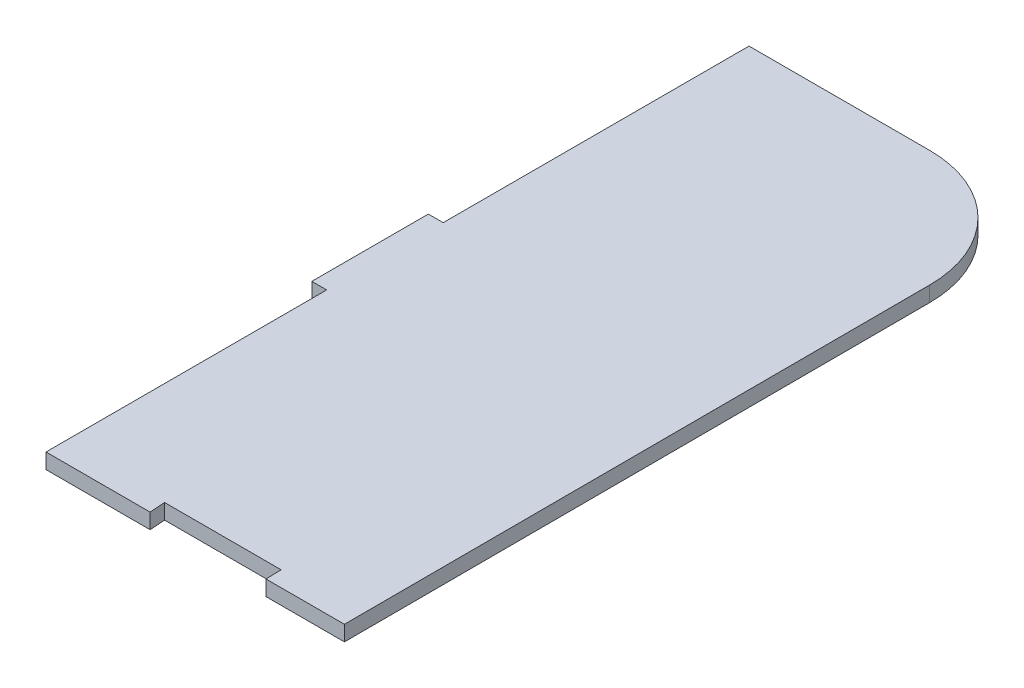
SolidWorks part; units mm, degrees
ref_plane "Front Plane" through (0, 0, 0) normal (0, 0, 1) x (1, 0, 0)
ref_plane "Top Plane" through (0, 0, 0) normal (0, 1, 0) x (1, 0, 0)
ref_plane "Right Plane" through (0, 0, 0) normal (1, 0, 0) x (0, 0, -1)
sketch "Sketch1" plane through (0, 0, 0) normal (0, 0, 1) x (1, 0, 0)
  line L0 (358.1218, 1488.44) -> (358.1218, 20.32) construction
  line L1 (358.1218, 754.38) -> (137.9613, 754.38)
  line L2 (358.1218, 754.38) -> (562.8036, 754.38)
  line L3 (562.8036, 754.38) -> (562.8036, 744.38)
  line L4 (562.8036, 744.38) -> (137.9613, 744.38)
  line L5 (137.9613, 744.38) -> (137.9613, 754.38)
  dimension "D1" = 10
extrude "Boss-Extrude1" add sketch "Sketch1" along normal up to surface (459.74 mm away)
sketch "Sketch3" plane through (0, 744.38, 0) normal (0, -1, 0) x (1, 0, 0)
  line L0 (255.63, 0) -> (255.63, 459.74)
  line L1 (137.9613, 0) -> (562.8036, 0) construction
  line L2 (137.9613, 459.74) -> (562.8036, 459.74) construction
  line L3 (255.63, 459.74) -> (137.9613, 459.74)
  line L4 (137.9613, 459.74) -> (137.9613, 0)
  line L5 (137.9613, 0) -> (255.63, 0)
extrude "Cut-Extrude1" cut sketch "Sketch3" against normal blind 10
sketch "Sketch4" plane through (0, 754.38, 0) normal (0, 1, 0) x (1, 0, 0)
  line L0 (265.3552, -459.74) -> (265.3552, -276.2)
  line L1 (562.8036, -459.74) -> (255.63, -459.74) construction
  line L2 (562.8036, 0) -> (255.63, 0) construction
  line L3 (265.3552, -459.74) -> (255.63, -459.74)
  line L4 (255.63, -459.74) -> (255.63, -276.2)
  line L5 (215.8296, -276.2) -> (265.3552, -276.2) construction
  line L6 (215.8296, -200) -> (265.3552, -200) construction
  line L7 (265.3552, -459.74) -> (255.63, -459.74)
  line L8 (265.3552, -276.2) -> (255.63, -276.2)
  line L9 (265.3552, -200) -> (255.63, -200)
  line L10 (255.63, -200) -> (255.63, 0)
  line L11 (265.3552, -200) -> (265.3552, 0)
  line L12 (333.4642, -459.74) -> (369.7619, -561.8393)
  line L13 (333.4642, -459.74) -> (332.7218, -449.58)
  line L14 (332.7218, -449.58) -> (408.9218, -449.58)
  line L15 (408.9218, -449.58) -> (409.2168, -459.74)
  line L16 (409.2168, -459.74) -> (460.5019, -459.74)
  line L17 (460.5019, -459.74) -> (459.7218, -76.2)
  line L18 (369.7619, -561.8393) -> (604.2472, -525.6685)
  line L19 (604.2472, -525.6685) -> (681.4814, 161.1092)
  line L20 (681.4814, 161.1092) -> (358.7401, 101.8465)
  line L21 (358.7401, 101.8465) -> (383.5218, 0)
  line L23 (265.3552, 0) -> (255.63, 0)
  line L24 (255.63, -200) -> (255.63, 0)
  arc A1 (459.7218, -76.2) -> (383.5218, 0) centre (383.5218, -76.2) ccw construction
  arc A2 (459.7218, -76.2) -> (383.5218, 0) centre (383.5218, -76.2) ccw
  line M2 (562.8036, 0) -> (255.63, 0)
  line M3 (255.63, 0) -> (255.63, -459.74)
  line M4 (255.63, -459.74) -> (562.8036, -459.74)
  line M5 (562.8036, -459.74) -> (562.8036, 0)
extrude "Cut-Extrude3" cut sketch "Sketch4" against normal blind 63 contours L0 L8 M3 M4 | L9 L11 M2 M3 | L20 L21 L12 L18 L19 M2 M5 M4
